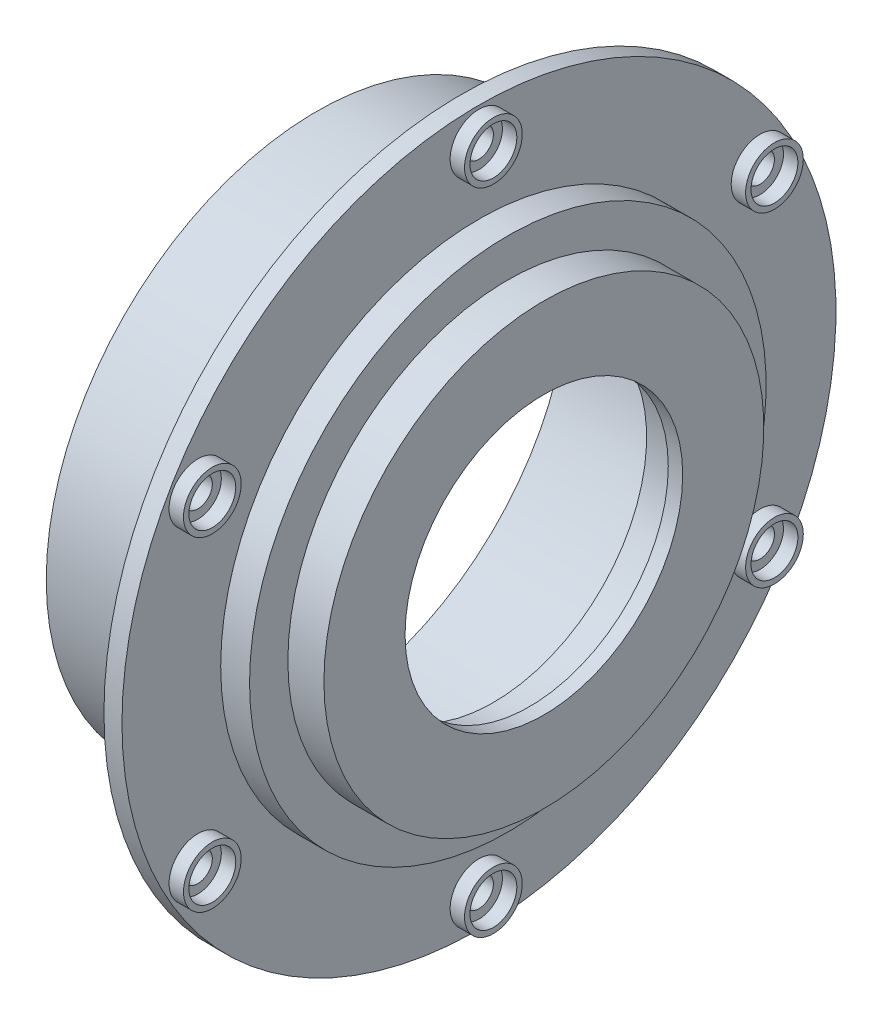
SolidWorks part; units mm, degrees
ref_plane "Front Plane" through (0, 0, 0) normal (0, 0, 1) x (1, 0, 0)
ref_plane "Top Plane" through (0, 0, 0) normal (0, 1, 0) x (1, 0, 0)
ref_plane "Right Plane" through (0, 0, 0) normal (1, 0, 0) x (0, 0, -1)
sketch "Sketch1" plane through (0, 0, 0) normal (0, 0, 1) x (1, 0, 0)
  line L0 (0, 5) -> (0, -70) construction
  line L1 (0, 0) -> (39, 0)
  line L2 (0, 0) -> (0, 5)
  line L3 (0, 5) -> (40, 5)
  line L5 (0, -70) -> (55.5444, -70) construction
  line L6 (39, 0) -> (39, -9)
  line L9 (40, 5) -> (40, 29)
  line L10 (40, 29) -> (45, 29)
  line L11 (39, -9) -> (49, -9)
  line L13 (49, -9) -> (49, -27.5)
  line L14 (49, -27.5) -> (59, -27.5)
  line L15 (59, -27.5) -> (59, -31.5)
  line L16 (59, -31.5) -> (63, -31.5)
  line L17 (63, -31.5) -> (63, -9)
  line L18 (63, -9) -> (53, -9)
  line L19 (53, -9) -> (53, 1.6237)
  line L20 (53, 1.6237) -> (45, 1.6237)
  line L21 (45, 29) -> (45, 1.6237)
revolve "Revolve1" add sketch "Sketch1" angle 360 about L5
sketch "Sketch3" plane through (45, 0, 0) normal (1, 0, 0) x (0, 0, -1)
  line L0 (0, -70) -> (0, 29) construction
  line L1 (0, 29) -> (0, 20) construction
  circle A0 centre (0, -70) radius 99 construction
  circle A1 centre (0, 20) radius 4
  circle A2 centre (77.9423, -25) radius 4
  circle A3 centre (77.9423, -115) radius 4
  circle A4 centre (0, -160) radius 4
  circle A5 centre (-77.9423, -115) radius 4
  circle A6 centre (-77.9423, -25) radius 4
  point P21 (0, -70)
  dimension "D1" = 8
  dimension "D2" = 6
extrude "Cut-Extrude1" cut sketch "Sketch3" against normal blind 10
sketch "Sketch4" plane through (45, 0, 0) normal (1, 0, 0) x (0, 0, -1)
  circle A1 centre (0, 20) radius 6.5
  circle A2 centre (77.9423, -25) radius 6.5
  circle A4 centre (77.9423, -115) radius 6.5
  circle A6 centre (0, -160) radius 6.5
  circle A8 centre (-77.9423, -115) radius 6.5
  circle A10 centre (-77.9423, -25) radius 6.5
  circle A13 centre (0, 20) radius 8
  circle A14 centre (77.9423, -25) radius 8
  circle A15 centre (77.9423, -115) radius 8
  circle A16 centre (0, -160) radius 8
  circle A17 centre (-77.9423, -115) radius 8
  circle A18 centre (-77.9423, -25) radius 8
  point P22 (0, -70)
  point P28 (0, -70)
  dimension "D1" = 13
  dimension "D3" = 16
  dimension "D2" = 6
  dimension "D4" = 6
extrude "Boss-Extrude1" add sketch "Sketch4" along normal blind 4
